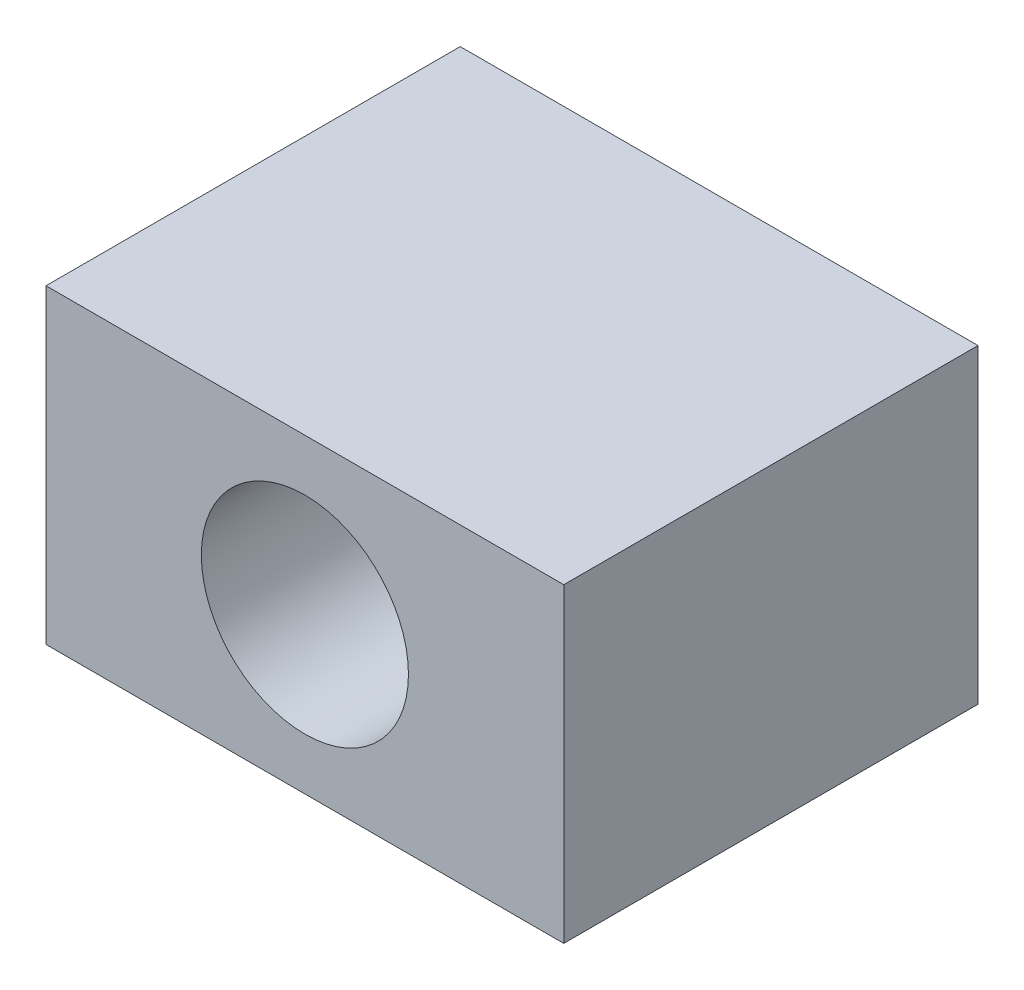
SolidWorks part; units mm, degrees
ref_plane "Front Plane" through (0, 0, 0) normal (0, 0, 1) x (1, 0, 0)
ref_plane "Top Plane" through (0, 0, 0) normal (0, 1, 0) x (1, 0, 0)
ref_plane "Right Plane" through (0, 0, 0) normal (1, 0, 0) x (0, 0, -1)
sketch "Sketch2" plane through (0, 0, 0) normal (0, 0, 1) x (1, 0, 0)
  line L1 (-2.5, 1.5) -> (2.5, 1.5)
  line L2 (-2.5, 1.5) -> (-2.5, -1.5)
  line L3 (-2.5, -1.5) -> (2.5, -1.5)
  line L4 (2.5, 1.5) -> (2.5, -1.5)
  line L5 (-2.5, 1.5) -> (2.5, -1.5) construction
  line L6 (-2.5, -1.5) -> (2.5, 1.5) construction
  point P0 (0, 0)
  dimension "D1" = 5
  dimension "D2" = 3
extrude "Boss-Extrude1" add sketch "Sketch2" along normal blind 4
sketch "Sketch3" plane through (0, 0, 4) normal (0, 0, 1) x (1, 0, 0)
  circle A0 centre (0, 0) radius 1
  dimension "D1" = 2
extrude "Cut-Extrude1" cut sketch "Sketch3" against normal blind 3
